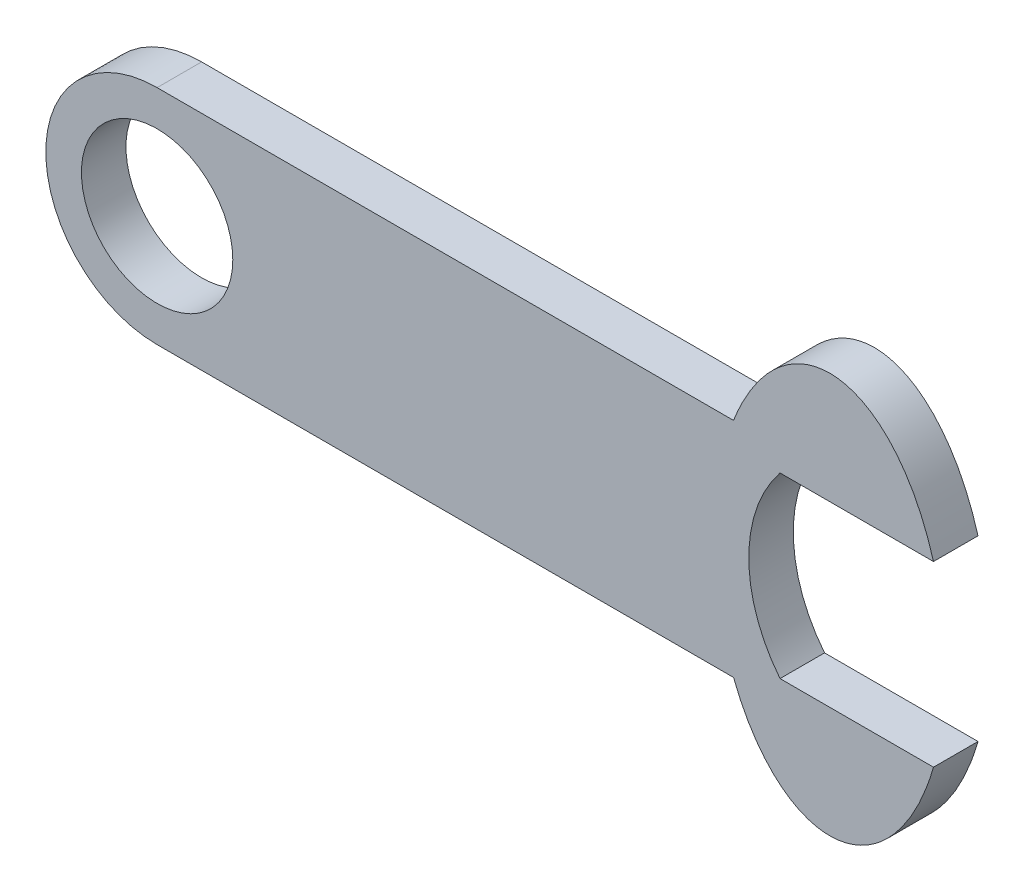
SolidWorks part; units mm, degrees
ref_plane "Ön Düzlem" through (0, 0, 0) normal (0, 0, 1) x (1, 0, 0)
ref_plane "Üst Düzlem" through (0, 0, 0) normal (0, 1, 0) x (1, 0, 0)
ref_plane "Sağ Düzlem" through (0, 0, 0) normal (1, 0, 0) x (0, 0, -1)
sketch "Çizim1" plane through (0, 0, 0) normal (0, 0, 1) x (1, 0, 0)
  line L0 (-50.5384, 0) -> (82.3616, 0) construction
  line L1 (-50.5384, 25) -> (78.9431, 25)
  line L2 (-50.5384, -25) -> (78.9431, -25)
  line L3 (114.3616, 58.1855) -> (114.3616, 20) construction
  line L4 (89.3816, 20) -> (123.8526, 20)
  line L6 (89.3816, -20) -> (123.8526, -20)
  line L8 (114.3616, -20) -> (114.3616, -82.3679) construction
  arc A0 (-50.5384, 25) -> (-50.5384, -25) centre (-50.5384, 0) ccw
  arc A1 (114.3616, -20.8461) -> (115.5616, -20) centre (100.5616, 0) ccw
  circle A2 centre (-50.5384, 0) radius 17
  arc A3 (89.3816, 20) -> (89.3816, -20) centre (114.3616, 0) ccw
  arc A4 (115.5616, 20) -> (114.3616, 20.8461) centre (100.5616, 0) ccw
  ellipse E0 centre (100.5616, 0) end of major axis (100.5616, 45) minor radius 26 (123.8526, 20) -> (78.9431, 25) ccw
  ellipse E1 centre (100.5616, 0) end of major axis (100.5616, 45) minor radius 26 (78.9431, -25) -> (123.8526, -20) ccw
  point P3 (25.0116, 0)
  dimension "D1" = 25
  dimension "D2" = 34
  dimension "D5" = 64
  dimension "D3" = 90
  dimension "D4" = 26
  dimension "D6" = 40
  dimension "D7" = 20
  dimension "D8" = 40
  dimension "D9" = 13.8
  dimension "D10" = 164.9
extrude "Yükseklik-Ekstrüzyon1" add sketch "Çizim1" along normal blind 10
